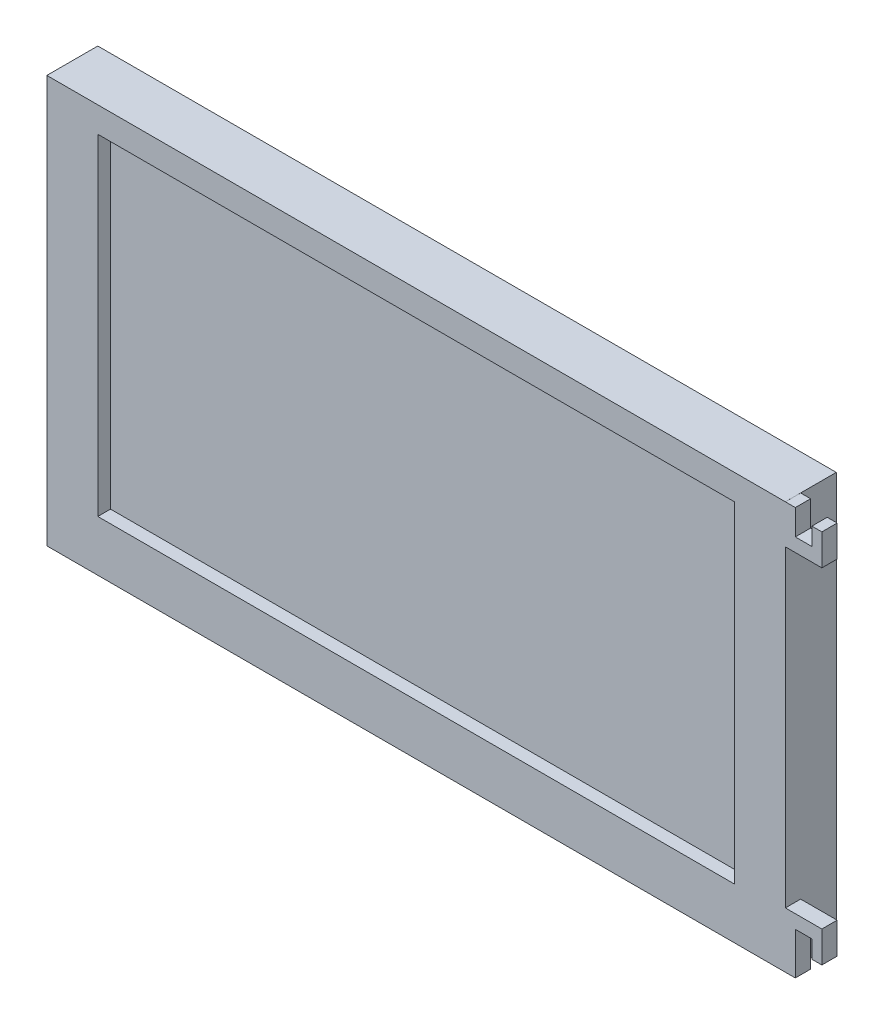
SolidWorks part; units mm, degrees
material "2024 Alloy"
ref_plane "Front Plane" through (0, 0, 0) normal (0, 0, 1) x (1, 0, 0)
ref_plane "Top Plane" through (0, 0, 0) normal (0, 1, 0) x (1, 0, 0)
ref_plane "Right Plane" through (0, 0, 0) normal (1, 0, 0) x (0, 0, -1)
sketch "Sketch1" plane through (0, 0, 0) normal (0, 0, 1) x (1, 0, 0)
  line L1 (-184.15, 101.6) -> (184.15, 101.6)
  line L2 (-184.15, 101.6) -> (-184.15, -101.6)
  line L3 (-184.15, -101.6) -> (184.15, -101.6)
  line L4 (184.15, 101.6) -> (184.15, -101.6)
  point P4 (0, 101.6)
  point P6 (-184.15, 0)
  dimension "D1" = 368.3
  dimension "D2" = 203.2
extrude "Boss-Extrude1" add sketch "Sketch1" along normal mid plane 25.4
sketch "Sketch2" plane through (0, 0, 12.7) normal (0, 0, 1) x (1, 0, 0)
  line L0 (-184.15, 101.6) -> (-184.15, -101.6) construction
  line L1 (-158.75, 88.9) -> (158.75, 88.9)
  line L2 (-158.75, 88.9) -> (-158.75, -76.2)
  line L3 (-158.75, -76.2) -> (158.75, -76.2)
  line L4 (158.75, 88.9) -> (158.75, -76.2)
  line L5 (184.15, 101.6) -> (-184.15, 101.6) construction
  line L6 (-184.15, -101.6) -> (184.15, -101.6) construction
  point P6 (0, 88.9)
  dimension "D1" = 25.4
  dimension "D2" = 12.7
  dimension "D3" = 25.4
extrude "Cut-Extrude1" cut sketch "Sketch2" against normal blind 6.35
sketch "Sketch4" plane through (0, 0, 12.7) normal (0, 0, 1) x (1, 0, 0)
  line L0 (184.15, -101.6) -> (184.15, 101.6) construction
  line L1 (184.15, -101.6) -> (189.1197, -101.6)
  line L2 (184.15, -101.6) -> (184.15, -73.8207)
  line L4 (189.1197, -101.6) -> (189.1197, -80.5602)
  line L5 (184.15, -73.8207) -> (202.3622, -73.8207)
  line L7 (189.1197, -80.5602) -> (197.3925, -80.5602)
  line L8 (202.3622, -73.8207) -> (202.3622, -89.3699)
  line L11 (202.3622, -89.3699) -> (197.3925, -89.3699)
  line L12 (197.3925, -80.5602) -> (197.3925, -89.3699)
  line L13 (189.1197, 88.9) -> (197.3925, 88.9)
  line L14 (184.15, 88.0126) -> (184.15, 82.1604)
  line L15 (184.15, 82.1604) -> (202.3622, 82.1604)
  line L19 (197.3925, 88.9) -> (197.3925, 97.7097)
  line L20 (197.3925, 97.7097) -> (202.3622, 97.7097)
  line L21 (202.3622, 82.1604) -> (202.3622, 97.7097)
  line L23 (184.15, 88.0126) -> (184.15, 101.5849)
  line L24 (184.15, 101.5849) -> (189.1197, 101.5849)
  line L25 (189.1197, 88.9) -> (189.1197, 101.5849)
  line L26 (184.15, 101.6) -> (-188.2833, 101.6) construction
  dimension "D1" = 12.7
extrude "Boss-Extrude3" add sketch "Sketch4" against normal blind 7.62
